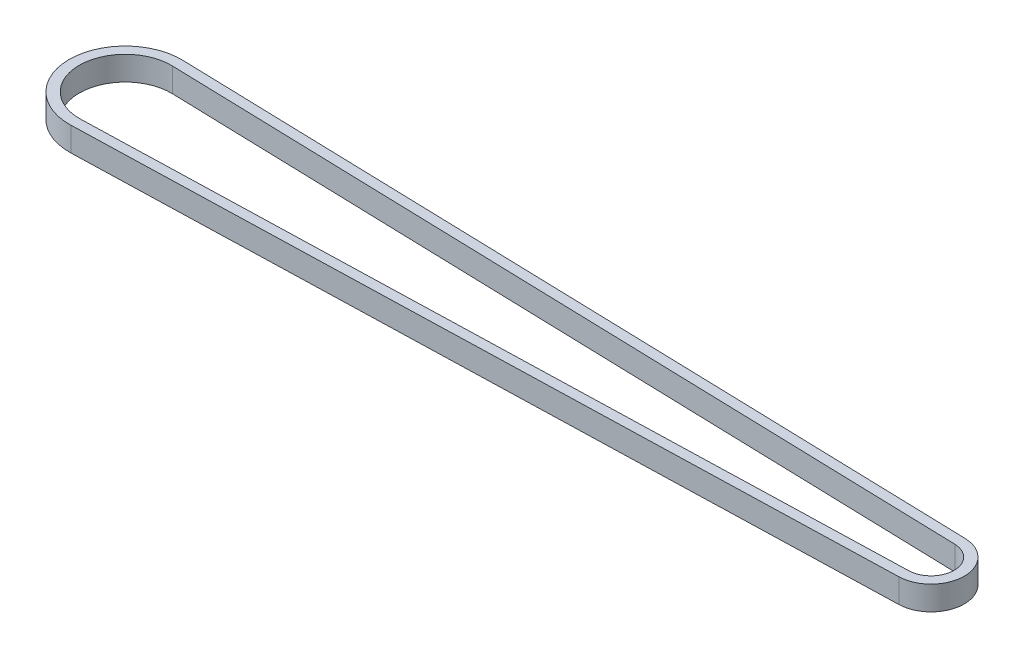
SolidWorks part; units mm, degrees
material "POLYURETHANE (11671)"
ref_plane "Front Plane" through (0, 0, 0) normal (0, 0, 1) x (1, 0, 0)
ref_plane "Top Plane" through (0, 0, 0) normal (0, 1, 0) x (1, 0, 0)
ref_plane "Right Plane" through (0, 0, 0) normal (1, 0, 0) x (0, 0, -1)
sketch "Sketch1" plane through (0, 0, 0) normal (0, 1, 0) x (1, 0, 0)
  line L0 (-100.33, 0) -> (100.33, 0) construction
  line L1 (0, 0) -> (0, 67523.6974) construction
  line L4 (-100.0031, 11.4507) -> (100.4935, 5.7266)
  line L5 (-100.0031, -11.4507) -> (100.4935, -5.7266)
  line L6 (0, 0) -> (0, 44.9411) construction
  line L7 (-99.9321, 13.9643) -> (100.5651, 8.2517)
  line L8 (-99.9321, -13.9643) -> (100.5651, -8.2517)
  arc A0 (-100.0031, 11.4507) -> (-100.0031, -11.4507) centre (-100.33, 0) ccw
  arc A1 (100.4935, -5.7266) -> (100.4935, 5.7266) centre (100.33, 0) ccw
  arc A2 (-99.9321, 13.9643) -> (-99.9321, -13.9643) centre (-100.33, 0) ccw
  arc A3 (100.5651, -8.2517) -> (100.5651, 8.2517) centre (100.33, 0) ccw
  dimension "D2" = 22.9108
  dimension "D3" = 11.4579
  dimension "D4" = 27.94
  dimension "D5" = 16.51
  dimension "D1" = 200.66
extrude "Boss-Extrude1" add sketch "Sketch1" along normal blind 5.9944
